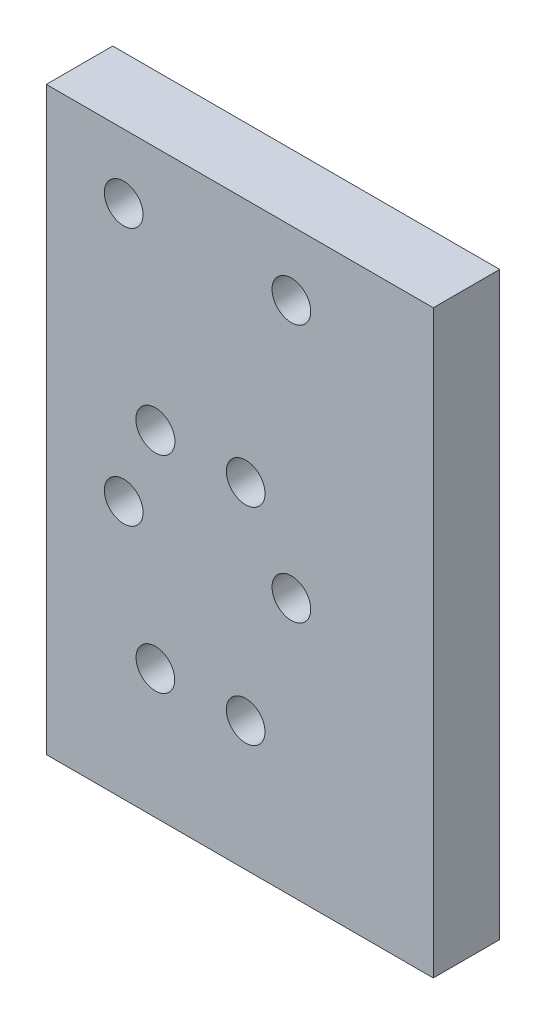
SolidWorks part; units mm, degrees
ref_plane "前视基准面" through (0, 0, 0) normal (0, 0, 1) x (1, 0, 0)
ref_plane "上视基准面" through (0, 0, 0) normal (0, 1, 0) x (1, 0, 0)
ref_plane "右视基准面" through (0, 0, 0) normal (1, 0, 0) x (0, 0, -1)
sketch "草图1" plane through (0, 0, 0) normal (0, 0, 1) x (1, 0, 0)
  line L1 (-23, -24.05) -> (-53, -24.05)
  line L2 (-23, -24.05) -> (-23, 20.95)
  line L3 (-23, 20.95) -> (-53, 20.95)
  line L4 (-53, -24.05) -> (-53, 20.95)
  point P5 (0, 0)
extrude "凸台-拉伸1" add sketch "草图1" along normal blind 5.15
sketch "草图2" plane through (0, 0, 5.15) normal (0, 0, 1) x (1, 0, 0)
  line L0 (-34, 15.95) -> (-47, 15.95) construction
  line L1 (-53, 20.95) -> (-53, -24.05) construction
  line L2 (-47, 15.95) -> (-47, 14.45) construction
  line L3 (-47, -4.05) -> (-34, -4.05) construction
  line L4 (-34, 14.45) -> (-34, 15.95) construction
  circle A0 centre (-34, 15.95) radius 1.5
  circle A1 centre (-47, 15.95) radius 1.5
  circle A3 centre (-34, -4.05) radius 1.5
  circle A4 centre (-47, -4.05) radius 1.5
  dimension "D1" = 3
  dimension "D3" = 3
  dimension "D4" = 3
  dimension "D2" = 6
  dimension "D5" = 13
extrude "切除-拉伸1" cut sketch "草图2" against normal through all both and the other way through all
sketch "草图3" plane through (0, 0, 5.15) normal (0, 0, 1) x (1, 0, 0)
  circle A0 centre (-44.5442, -14.05) radius 1.5
  circle A1 centre (-37.5442, -14.05) radius 1.5
  circle A2 centre (-44.5442, 1.95) radius 1.5138
  circle A3 centre (-37.5442, 1.95) radius 1.5
extrude "切除-拉伸2" cut sketch "草图3" against normal through all both and the other way through all
